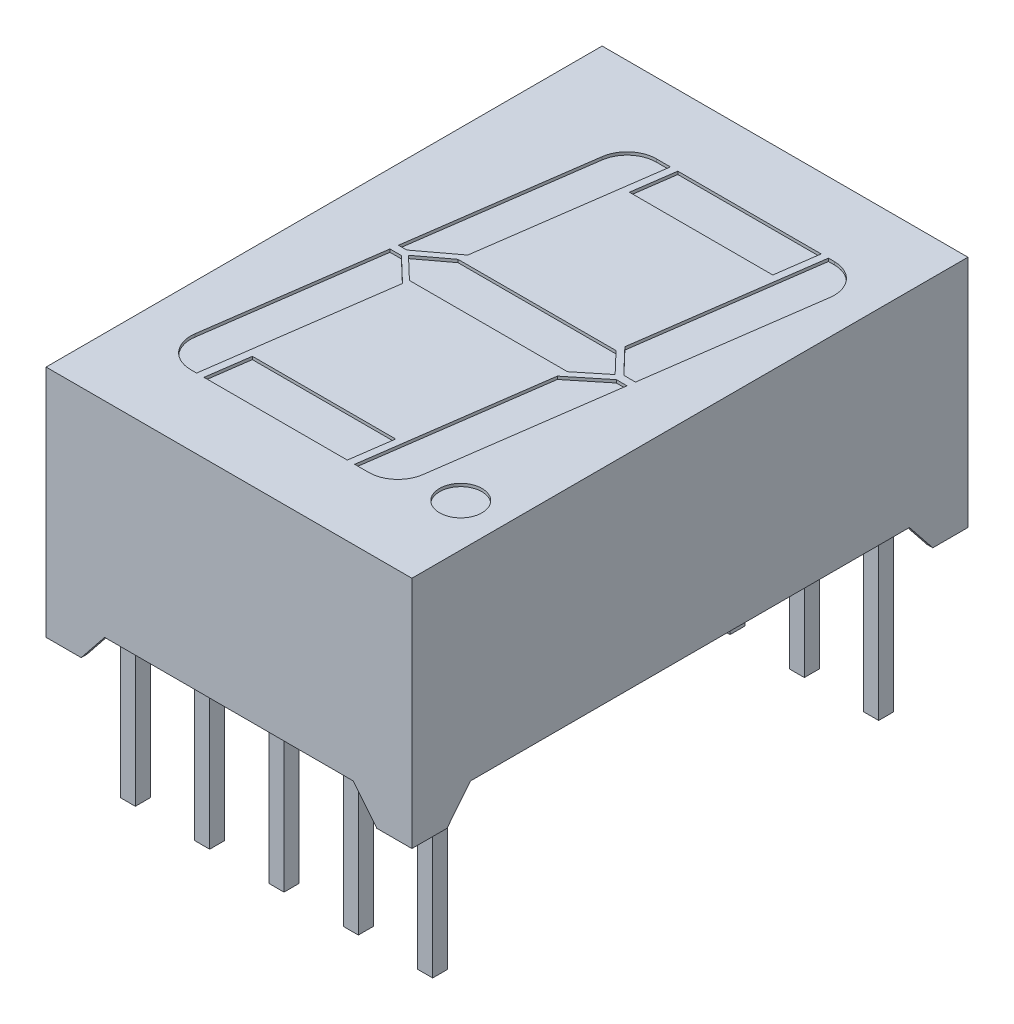
SolidWorks part; units mm, degrees
ref_plane "Alzado" through (0, 0, 0) normal (0, 0, 1) x (1, 0, 0)
ref_plane "Planta" through (0, 0, 0) normal (0, 1, 0) x (1, 0, 0)
ref_plane "Vista lateral" through (0, 0, 0) normal (1, 0, 0) x (0, 0, -1)
sketch "Croquis1" plane through (0, 0, 0) normal (0, 1, 0) x (1, 0, 0)
  line L0 (0, 0) -> (0, 6.452) construction
  line L2 (-6.25, 9.5) -> (6.25, 9.5)
  line L3 (-6.25, 9.5) -> (-6.25, -9.5)
  line L4 (-6.25, -9.5) -> (6.25, -9.5)
  line L5 (6.25, 9.5) -> (6.25, -9.5)
  line L6 (-6.25, 9.5) -> (6.25, -9.5) construction
  line L7 (-6.25, -9.5) -> (6.25, 9.5) construction
  dimension "D1" = 12.5
  dimension "D2" = 19
extrude "Saliente-Extruir1" add sketch "Croquis1" along normal blind 8
sketch "Croquis4" plane through (0, 0, 0) normal (0, 1, 0) x (1, 0, 0)
  line L0 (-6.25, 9.5) -> (-6.25, -9.5) construction
  line L1 (6.05, 9.3) -> (-6.05, 9.3)
  line L2 (6.05, 9.3) -> (6.05, -9.3)
  line L3 (6.05, -9.3) -> (-6.05, -9.3)
  line L4 (-6.05, 9.3) -> (-6.05, -9.3)
  line L5 (6.05, 9.3) -> (-6.05, -9.3) construction
  line L6 (6.05, -9.3) -> (-6.05, 9.3) construction
  line L7 (6.25, 9.5) -> (-6.25, 9.5) construction
  point P0 (0, 0)
  dimension "D1" = 0.2
  dimension "D2" = 0.2
extrude "Cortar-Extruir3" cut sketch "Croquis4" along normal blind 1 contours L2 L1 L4 L3
sketch "Croquis2" plane through (6.25, 0, 0) normal (1, 0, 0) x (0, 0, -1)
  line L0 (0, 0) -> (0, 4.6782) construction
  line L1 (9.5, 0) -> (8.3, 0)
  line L2 (-9.5, 0) -> (9.5, 0) construction
  line L3 (8.3, 0) -> (7.5, 1)
  line L4 (7.5, 1) -> (-7.5, 1)
  line L5 (9.5, 8) -> (9.5, 0) construction
  line L6 (8.3, 0) -> (-8.3, 0)
  line L7 (-8.3, 0) -> (-7.5, 1)
  point P14 (0, 1)
  line M7 (-9.5, 0) -> (9.5, 0)
  dimension "D1" = 1.2
  dimension "D2" = 2
  dimension "D3" = 1
extrude "Cortar-Extruir1" cut sketch "Croquis2" against normal through all contours L0 L4 L7 M7 | L0 L6 L3 L4
sketch "Croquis3" plane through (0, 0, 9.5) normal (0, 0, 1) x (1, 0, 0)
  line L0 (0, 0) -> (0, 4.4674) construction
  line L1 (-6.25, 0) -> (6.25, 0) construction
  line L2 (-4.25, 1) -> (4.25, 1)
  line L3 (4.25, 1) -> (5.05, 0)
  line L4 (5.05, 0) -> (6.25, 0)
  line L5 (6.25, 8) -> (6.25, 0) construction
  line L6 (5.05, 0) -> (-5.05, 0)
  line L7 (-4.25, 1) -> (-5.05, 0)
  point P13 (0, 1)
  line M6 (-6.25, 0) -> (6.25, 0)
  dimension "D1" = 1.2
  dimension "D2" = 1
  dimension "D3" = 2
extrude "Cortar-Extruir2" cut sketch "Croquis3" against normal through all contours L0 L6 L3 L2 | L0 L2 L7 M6
sketch "Croquis5" plane through (0, 1, 0) normal (0, -1, 0) x (1, 0, 0)
  line L1 (-6.05, 9.3) -> (6.05, 9.3)
  line L2 (-6.05, 9.3) -> (-6.05, -9.3)
  line L3 (-6.05, -9.3) -> (6.05, -9.3)
  line L4 (6.05, 9.3) -> (6.05, -9.3)
  line L5 (-6.05, 9.3) -> (6.05, -9.3) construction
  line L6 (-6.05, -9.3) -> (6.05, 9.3) construction
  point P0 (0, 0)
extrude "Cortar-Extruir4" cut sketch "Croquis5" against normal blind 0.2
sketch "Croquis6" plane through (0, 1.2, 0) normal (0, -1, 0) x (1, 0, 0)
  line L0 (0, 0) -> (10.8366, 0) construction
  line L1 (4.825, 7.875) -> (5.335, 7.875)
  line L2 (4.825, 7.875) -> (4.825, 7.365)
  line L3 (4.825, 7.365) -> (5.335, 7.365)
  line L4 (5.335, 7.875) -> (5.335, 7.365)
  line L5 (4.825, 7.875) -> (5.335, 7.365) construction
  line L6 (4.825, 7.365) -> (5.335, 7.875) construction
  line L7 (0, 7.845) -> (0, 10.5529) construction
  line L8 (-4.825, 7.875) -> (-4.825, 7.365)
  line L9 (-4.825, 7.875) -> (-5.335, 7.875)
  line L10 (-5.335, 7.875) -> (-5.335, 7.365)
  line L11 (-4.825, 7.365) -> (-5.335, 7.365)
  line L13 (-2.285, 7.365) -> (-2.795, 7.365)
  line L14 (-2.285, 7.875) -> (-2.285, 7.365)
  line L15 (-2.285, 7.875) -> (-2.795, 7.875)
  line L16 (-2.795, 7.875) -> (-2.795, 7.365)
  line L17 (0.255, 7.365) -> (-0.255, 7.365)
  line L18 (0.255, 7.875) -> (0.255, 7.365)
  line L19 (0.255, 7.875) -> (-0.255, 7.875)
  line L20 (-0.255, 7.875) -> (-0.255, 7.365)
  line L21 (2.795, 7.365) -> (2.285, 7.365)
  line L22 (2.795, 7.875) -> (2.795, 7.365)
  line L23 (2.795, 7.875) -> (2.285, 7.875)
  line L24 (2.285, 7.875) -> (2.285, 7.365)
  line L25 (4.825, -7.365) -> (5.335, -7.365)
  line L26 (4.825, -7.875) -> (4.825, -7.365)
  line L27 (4.825, -7.875) -> (5.335, -7.365) construction
  line L28 (4.825, -7.365) -> (5.335, -7.875) construction
  line L29 (4.825, -7.875) -> (5.335, -7.875)
  line L30 (5.335, -7.875) -> (5.335, -7.365)
  line L31 (2.795, -7.875) -> (2.795, -7.365)
  line L32 (2.795, -7.875) -> (2.285, -7.875)
  line L33 (2.285, -7.875) -> (2.285, -7.365)
  line L34 (2.795, -7.365) -> (2.285, -7.365)
  line L35 (0.255, -7.875) -> (0.255, -7.365)
  line L36 (0.255, -7.875) -> (-0.255, -7.875)
  line L37 (-0.255, -7.875) -> (-0.255, -7.365)
  line L38 (0.255, -7.365) -> (-0.255, -7.365)
  line L39 (-2.795, -7.875) -> (-2.795, -7.365)
  line L40 (-2.285, -7.875) -> (-2.795, -7.875)
  line L41 (-2.285, -7.875) -> (-2.285, -7.365)
  line L42 (-2.285, -7.365) -> (-2.795, -7.365)
  line L43 (-4.825, -7.365) -> (-5.335, -7.365)
  line L44 (-4.825, -7.875) -> (-5.335, -7.875)
  line L45 (-4.825, -7.875) -> (-4.825, -7.365)
  line L46 (-5.335, -7.875) -> (-5.335, -7.365)
  point P0 (5.08, 7.62)
  point P13 (-5.08, 7.875)
  point P14 (5.08, -7.62)
  dimension "D1" = 0.51
  dimension "D2" = 0.51
  dimension "D3" = 10.16
  dimension "D4" = 15.24
  dimension "D5" = 4
extrude "Saliente-Extruir2" add sketch "Croquis6" along normal blind 6.3
sketch "Croquis7" plane through (0, 8, 0) normal (0, 1, 0) x (1, 0, 0)
  line L0 (0, -7.0896) -> (0, 7.0896) construction
  line L1 (0, 0) -> (5.7583, 0) construction
  line L2 (-1.9861, 7.0896) -> (-1.5054, 7.0896)
  line L3 (0, 5.6396) -> (3.4418, 5.6396)
  line L4 (5.0846, 5.9504) -> (4.2661, 0.125)
  line L5 (4.0943, 7.0896) -> (3.8946, 7.0896)
  line L6 (3.8946, 7.0896) -> (3.0376, 0.9897)
  line L7 (1.9, -7.1069) -> (2.3807, -7.1069)
  line L8 (3.6455, 7.0896) -> (3.4418, 5.6396)
  line L9 (1.65, -7.1069) -> (-3.2475, -7.1069)
  line L10 (1.65, -7.1069) -> (1.8537, -5.6569)
  line L11 (1.8537, -5.6569) -> (-3.0438, -5.6569)
  line L12 (-3.0438, -5.6569) -> (-3.2475, -7.1069)
  line L15 (0, 0.725) -> (3.0004, 0.725)
  line L16 (3.0004, 0.725) -> (3.695, 0)
  line L17 (4.2661, 0.125) -> (3.8661, 0.125)
  line L18 (4.2303, -0.13) -> (3.8661, -0.13)
  line L19 (3.8661, 0.125) -> (3.0376, 0.9897)
  line L20 (0, -0.73) -> (2.796, -0.73)
  line L21 (3.8661, -0.13) -> (2.7533, -1.0335)
  line L22 (6.25, -9.5) -> (6.25, 9.5) construction
  line L23 (3.695, 0) -> (2.796, -0.73)
  line L24 (0, 0.725) -> (-2.3996, 0.725)
  line L25 (-2.9763, 6.2287) -> (-3.8339, 0.125)
  line L26 (-1.5054, 7.0896) -> (-2.3584, 1.0184)
  line L27 (-1.5054, 7.0896) -> (-1.9861, 7.0896)
  line L28 (-3.6997, -7.1069) -> (-3.5, -7.1069)
  line L29 (0, 7.0896) -> (3.6455, 7.0896)
  line L30 (0, 7.0896) -> (-1.2529, 7.0896)
  line L31 (-1.2529, 7.0896) -> (-1.4567, 5.6396)
  line L32 (-1.4567, 5.6396) -> (0, 5.6396)
  line L33 (0, -0.73) -> (-2.604, -0.73)
  line L34 (-3.8339, 0.125) -> (-3.5496, 0.125)
  line L35 (-3.8697, -0.13) -> (-3.4769, -0.13)
  line L36 (0, 0) -> (-4.5272, 0) construction
  line L37 (-3.5496, 0.125) -> (-2.3584, 1.0184)
  line L39 (-2.3996, 0.725) -> (-3.3663, 0)
  line L40 (3.0004, 0.725) -> (2.796, -0.73)
  line L41 (-3.4769, -0.13) -> (-2.6333, -0.938)
  line L42 (-3.3663, 0) -> (-2.604, -0.73)
  line L43 (2.7533, -1.0335) -> (1.9, -7.1069)
  line L44 (4.2303, -0.13) -> (3.371, -6.2461)
  line L45 (-2.3996, 0.725) -> (-2.604, -0.73)
  line L46 (-2.6333, -0.938) -> (-3.5, -7.1069)
  line L47 (-3.8697, -0.13) -> (-4.69, -5.9678)
  circle A0 centre (4.7878, -6.368) radius 0.725
  arc A1 (-3.6997, -7.1069) -> (-4.69, -5.9678) centre (-3.6997, -6.1069) cw
  arc A2 (-2.9763, 6.2287) -> (-1.9861, 7.0896) centre (-1.9861, 6.0896) cw
  arc A3 (2.3807, -7.1069) -> (3.371, -6.2461) centre (2.3807, -6.1069) ccw
  arc A4 (5.0846, 5.9504) -> (4.0943, 7.0896) centre (4.0943, 6.0896) ccw
  point P9 (0, 5.6396)
  point P56 (3.25, -7.1069)
  point P59 (5.2446, 7.0896)
  dimension "D10" = 14.1965
  dimension "D11" = 1.45
  dimension "D23" = 1
  dimension "D2" = 1.45
  dimension "D3" = 3
  dimension "D4" = 0.25
  dimension "D5" = 1.35
  dimension "D6" = 0.73
  dimension "D7" = 0.25
  dimension "D8" = 0.25
  dimension "D9" = 1.45
  dimension "D12" = 0.725
  dimension "D13" = 0.125
  dimension "D14" = 0.4
  dimension "D15" = 0.13
  dimension "D16" = 0.2088
  dimension "D17" = 0.21
  dimension "D18" = 0.2466
  dimension "D19" = 2
  dimension "D20" = 0.21
  dimension "D21" = 0.21
extrude "Cortar-Extruir5" cut sketch "Croquis7" against normal blind 0.1 contours L4 A4 L5 L6 L19 L17 | L7 A3 L44 L18 L21 L43 | L24 L45 L33 L20 L40 L15 | L11 L12 L9 L10 | A1 L28 L46 L41 L35 L47 | A2 L25 L34 L37 L26 L2 | L45 L39 L42 | L16 L40 L23 | A0 | L31 L32 L3 L8 L29 L30
